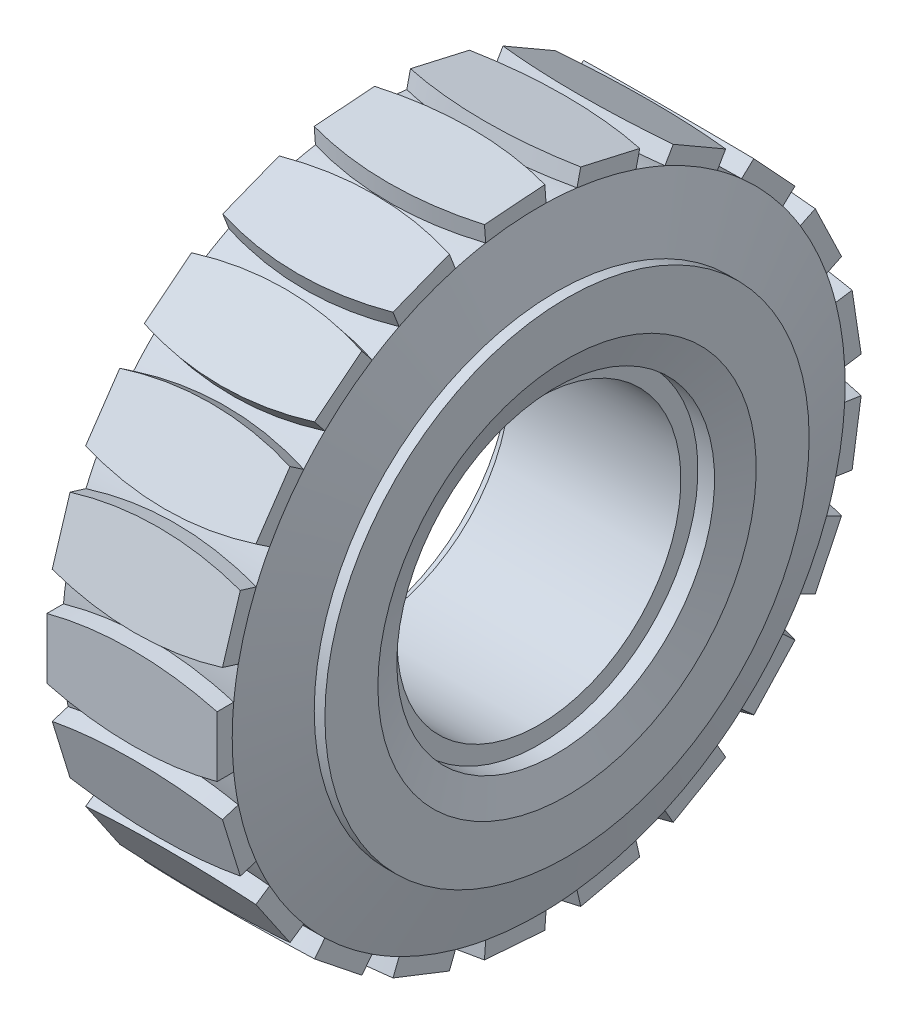
SolidWorks part; units mm, degrees
ref_plane "Front Plane" through (0, 0, 0) normal (0, 0, 1) x (1, 0, 0)
ref_plane "Top Plane" through (0, 0, 0) normal (0, 1, 0) x (1, 0, 0)
ref_plane "Right Plane" through (0, 0, 0) normal (1, 0, 0) x (0, 0, -1)
sketch "Sketch1" plane through (0, 0, 0) normal (0, 0, 1) x (1, 0, 0)
  line L0 (0, 20.25) -> (0, 0) construction
  line L1 (0, 0) -> (31.039, 0) construction
  line L2 (0, 9.375) -> (0, 20.25)
  line L3 (0, 20.25) -> (5.625, 20.25)
  line L4 (5.625, 20.25) -> (6.7938, 16)
  line L5 (6.7938, 16) -> (7.5, 16)
  line L6 (7.5, 16) -> (7.5, 12.5)
  line L7 (7.5, 12.5) -> (6.75, 10.5)
  line L8 (6.75, 10.5) -> (5.65, 10.5)
  line L9 (5.65, 10.5) -> (5.65, 9.375)
  line L10 (5.65, 9.375) -> (0, 9.375)
  line L11 (0, 20.25) -> (0, 21.5)
  line L12 (0, 21.5) -> (6.125, 21)
  line L13 (6.125, 21) -> (7.5, 16)
  dimension "D1" = 21.5
  dimension "D2" = 21
  dimension "D3" = 20.25
  dimension "D4" = 16
  dimension "D5" = 12.5
  dimension "D6" = 10.5
  dimension "D7" = 9.375
  dimension "D8" = 1.1
  dimension "D9" = 6.75
  dimension "D10" = 5.625
  dimension "D11" = 7.5
  dimension "D12" = 6.125
revolve "Revolve1" add sketch "Sketch1" angle 360 about L1
mirror "Mirror1" about plane through (0, 0, 0) normal (1, 0, 0) of bodies 101 113
ref_plane "Plane1" through (0, 0, 20.25) normal (0, 0, 1) x (1, 0, 0)
sketch "Sketch5" plane through (0, 0, 20.25) normal (0, 0, 1) x (1, 0, 0)
  line L0 (5.625, 20.25) -> (5.625, -20.25) construction
  line L1 (0, 0) -> (3.1655, 0) construction
  line L2 (-5.625, 2) -> (-5.625, -2)
  line L4 (5.625, 2) -> (5.625, -2)
  line L5 (-5.625, 2) -> (5.625, -2) construction
  line L6 (-5.625, -2) -> (5.625, 2) construction
  arc A0 (-5.625, 2) -> (5.625, 2) centre (0, -19.2687) cw
  arc A1 (-5.625, -2) -> (5.625, -2) centre (0, 19.2687) ccw
  point P0 (0, 0)
  dimension "D2" = 22
  dimension "D1" = 4
extrude "Boss-Extrude2" add sketch "Sketch5" along normal blind 1 and the other way up to next
pattern_circular "CirPattern2" count 21 over 360 about axis through (0, 0, 0) along (1, 0, 0) of "Boss-Extrude2"
